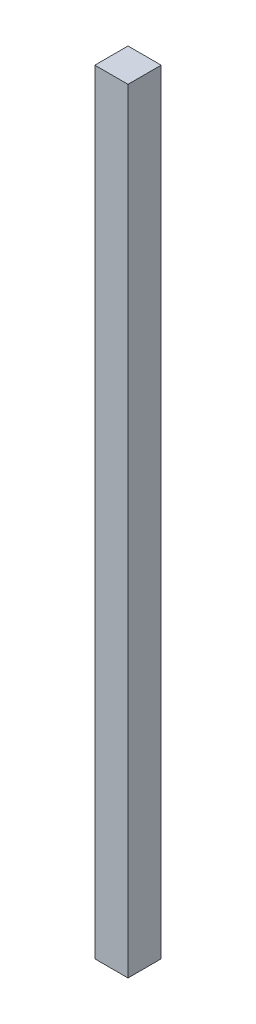
SolidWorks part; units mm, degrees
ref_plane "Front Plane" through (0, 0, 0) normal (0, 0, 1) x (1, 0, 0)
ref_plane "Top Plane" through (0, 0, 0) normal (0, 1, 0) x (1, 0, 0)
ref_plane "Right Plane" through (0, 0, 0) normal (1, 0, 0) x (0, 0, -1)
sketch "Sketch1" plane through (0, 0, 0) normal (0, 1, 0) x (1, 0, 0)
  line L1 (0, 0) -> (38.1, 0)
  line L2 (0, 0) -> (0, -38.1)
  line L3 (0, -38.1) -> (38.1, -38.1)
  line L4 (38.1, 0) -> (38.1, -38.1)
  dimension "D1" = 38.1
  dimension "D2" = 38.1
extrude "Boss-Extrude1" add sketch "Sketch1" along normal blind 889
